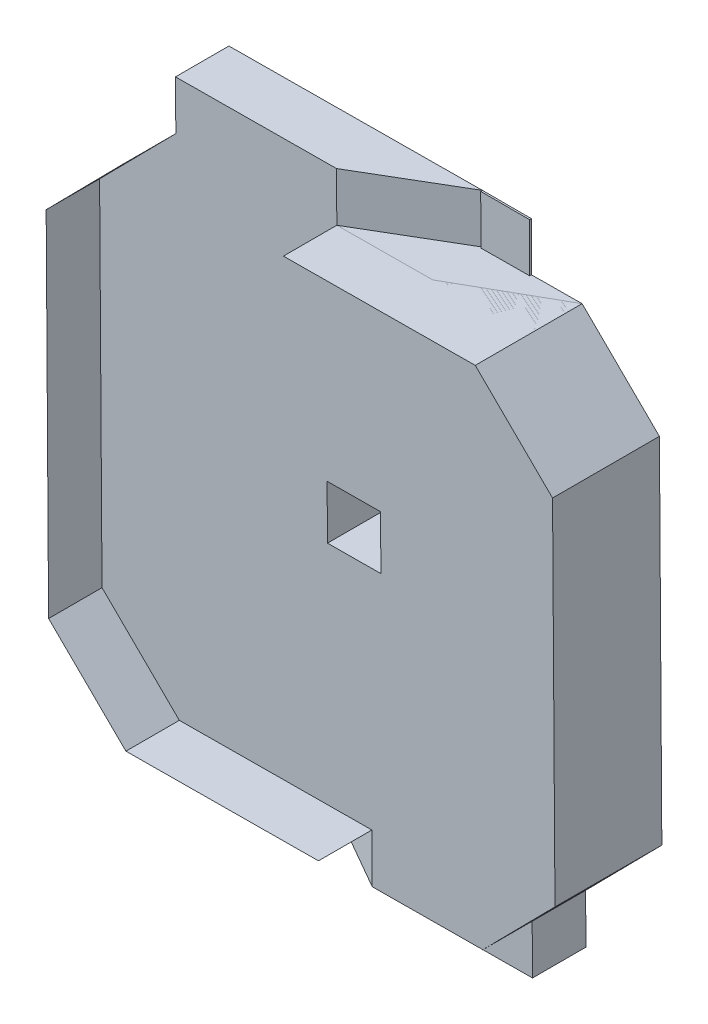
SolidWorks part; units mm, degrees
ref_plane "Front Plane" through (0, 0, 0) normal (0, 0, 1) x (1, 0, 0)
ref_plane "Top Plane" through (0, 0, 0) normal (0, 1, 0) x (1, 0, 0)
ref_plane "Right Plane" through (0, 0, 0) normal (1, 0, 0) x (0, 0, -1)
sketch "Sketch6" plane through (0, 0, 0) normal (0, 0, 1) x (1, 0, 0)
  line L1 (2687.6622, -1666.7646) -> (2660.3407, 2295.6354)
  line L2 (2660.3407, 2295.6354) -> (1792.3123, 3151.7753)
  line L3 (1792.3123, 3151.7753) -> (-2170.0877, 3124.4538)
  line L4 (-2170.0877, 3124.4538) -> (-3026.2275, 2256.4255)
  line L5 (-3026.2275, 2256.4255) -> (-2998.906, -1705.9745)
  line L6 (-2998.906, -1705.9745) -> (-2130.8777, -2562.1144)
  line L7 (-2130.8777, -2562.1144) -> (1831.5223, -2534.7929)
  line L8 (1831.5223, -2534.7929) -> (2687.6622, -1666.7646)
  dimension "D1" = 3962.4
  dimension "D2" = 1219.2
  dimension "D3" = 3962.4
  dimension "D4" = 1219.2
  dimension "D5" = 1219.2
  dimension "D6" = 1219.2
  dimension "D7" = 3962.4
  dimension "D8" = 3962.4
extrude "Boss-Extrude1" add sketch "Sketch6" along normal blind 600
sketch "Sketch7" plane through (-21.6458, 3139.2677, 0) normal (-0.0069, 1, 0) x (1, 0.0069, 0)
  line L0 (698.7813, 0) -> (-340.4492, -600)
  line L1 (1814.0013, 0) -> (-2148.4929, 0) construction
  line L2 (1814.0013, -600) -> (-2148.4929, -600) construction
  line L3 (698.7813, 0) -> (-2148.4929, 0)
  line L4 (-2148.4929, 0) -> (-2148.4929, -600)
  line L5 (-2148.4929, -600) -> (-340.4492, -600)
  dimension "D1" = 30
  dimension "D3" = 1115.22
extrude "Boss-Extrude2" add sketch "Sketch7" along normal blind 550
sketch "Sketch10" plane through (17.5641, -2547.3005, 0) normal (0.0069, -1, 0) x (1, 0.0069, 0)
  line L0 (1814.0013, 600) -> (14.0013, 600)
  line L1 (-2148.4929, 600) -> (1814.0013, 600) construction
  line L2 (14.0013, 600) -> (-1025.2292, 0)
  line L3 (-2148.4929, 0) -> (1814.0013, 0) construction
  line L4 (-1025.2292, 0) -> (1814.0013, 0)
  line L5 (1814.0013, 0) -> (1814.0013, 600)
  dimension "D1" = 1800
  dimension "D2" = 30
extrude "Boss-Extrude4" add sketch "Sketch10" along normal blind 550
sketch "Sketch18" plane through (0, 0, 0) normal (0, 0, -1) x (-1, 0, 0)
  line L0 (-677.1189, 3144.0858) -> (-673.3266, 3694.0727)
  line L1 (-673.3266, 3694.0727) -> (-1223.3266, 3694.0727)
  line L2 (-1223.3266, 3694.0727) -> (-1223.3266, 3147.852)
  line L3 (-1792.3123, 3151.7753) -> (-677.1189, 3144.0858) construction
  line L4 (-1223.3266, 3147.852) -> (-677.1189, 3144.0858)
  line L5 (1007.6407, -2554.3695) -> (1003.8484, -3104.3564)
  line L6 (1003.8484, -3104.3564) -> (1553.8484, -3108.1487)
  line L7 (1553.8484, -3108.1487) -> (1553.8484, -2558.1357)
  line L8 (2130.8777, -2562.1144) -> (1007.6407, -2554.3695) construction
  line L9 (1553.8484, -2558.1357) -> (1007.6407, -2554.3695)
  dimension "D1" = 550
  dimension "D2" = 550
extrude "Boss-Extrude15" add sketch "Sketch18" against normal blind 20 from surface at 0 separate body starting at face at (-168.1336, 294.8384, 0)
sketch "Sketch22" plane through (0, 0, 600) normal (0, 0, 1) x (1, 0, 0)
  line L1 (128.6417, 596.8918) -> (-471.3441, 592.7548)
  line L2 (128.6417, 596.8918) -> (132.7787, -3.0939)
  line L3 (132.7787, -3.0939) -> (-467.207, -7.2309)
  line L4 (-471.3441, 592.7548) -> (-467.207, -7.2309)
  point P0 (-134.072, 324.4092)
  dimension "D1" = 600
  dimension "D2" = 600
extrude "Cut-Extrude1" cut sketch "Sketch22" against normal blind 1000
sketch "Sketch23" plane through (0, 0, 600) normal (0, 0, 1) x (1, 0, 0)
  line L1 (2687.6622, -1666.7646) -> (2660.3407, 2295.6354) construction
  line L3 (1792.3123, 3151.7753) -> (-362.0869, 3136.9203) construction
  line L9 (-2170.0877, 3124.4538) -> (-3026.2275, 2256.4255)
  line L11 (-3026.2275, 2256.4255) -> (-2998.906, -1705.9745)
  line L12 (-2998.906, -1705.9745) -> (-2130.8777, -2562.1144)
  line L13 (-2130.8777, -2562.1144) -> (31.5651, -2547.2039)
  line L15 (1831.5223, -2534.7929) -> (2687.6622, -1666.7646)
  line L16 (2687.6622, -1666.7646) -> (2660.3407, 2295.6354)
  line L17 (2660.3407, 2295.6354) -> (1792.3123, 3151.7753)
  line L19 (-2170.0877, 3124.4538) -> (-3026.2275, 2256.4255) construction
  line L20 (35.3573, -3097.1909) -> (31.5651, -2547.2039) construction
  line L21 (1792.3123, 3151.7753) -> (-362.0869, 3136.9203)
surface "Surface-Extrude3" sketch "Sketch23" parameters "D1"=600, "D2"=600
